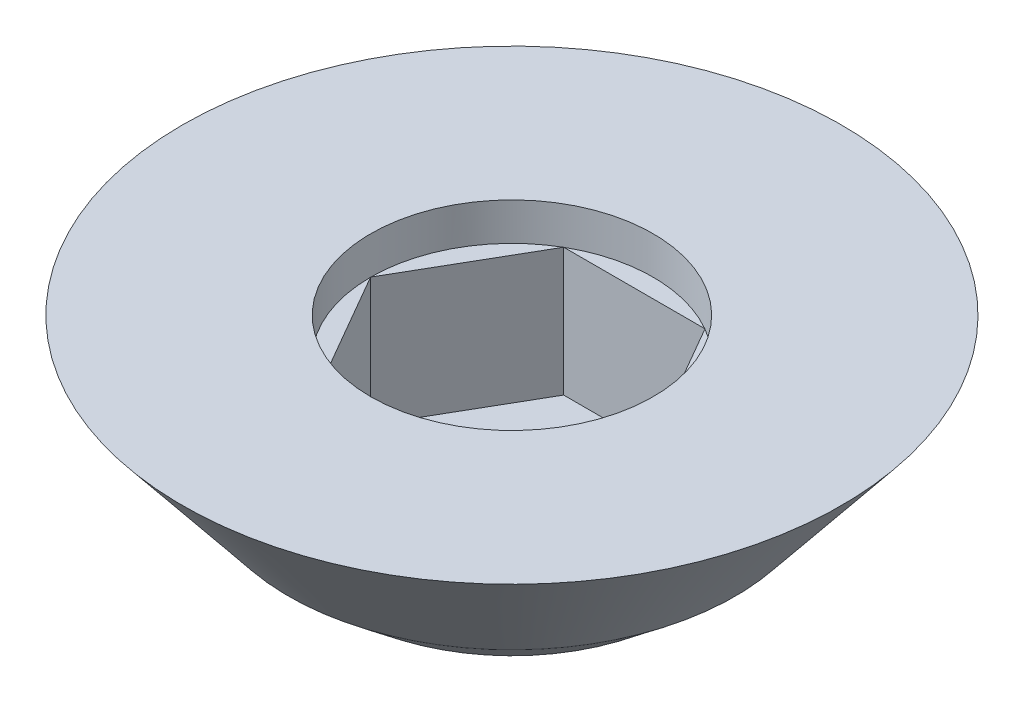
SolidWorks part; units mm, degrees
material "ABS"
ref_plane "Piano frontale" through (0, 0, 0) normal (0, 0, 1) x (1, 0, 0)
ref_plane "Piano superiore" through (0, 0, 0) normal (0, 1, 0) x (1, 0, 0)
ref_plane "Piano destro" through (0, 0, 0) normal (1, 0, 0) x (0, 0, -1)
sketch "Schizzo3" plane through (0, 0, 0) normal (0, 0, 1) x (1, 0, 0)
  line L0 (0, 0) -> (-10, 0) construction
  line L1 (-10, 0) -> (-17.5, 9.3) construction
  line L2 (-17.5, 9.3) -> (0, 9.3)
  line L3 (0, 9.3) -> (0, 0)
  line L4 (-11.8502, 2.2943) -> (-9, 0)
  line L5 (-11.8502, 2.2943) -> (-17.5, 9.3)
  line L6 (-9, 0) -> (0, 0)
  dimension "D1" = 9.3
  dimension "D2" = 10
  dimension "D3" = 17.5
  dimension "D4" = 9
  dimension "D5" = 9
revolve "Rivoluzione1" add sketch "Schizzo3" angle 360 about L3
sketch "Schizzo4" plane through (0, 9.3, 0) normal (0, 1, 0) x (1, 0, 0)
  circle A0 centre (0, 0) radius 7.5
  dimension "D1" = 15
extrude "Taglio-Estrusione1" cut sketch "Schizzo4" against normal blind 2
sketch "Schizzo5" plane through (0, 7.3, 0) normal (0, 1, 0) x (1, 0, 0)
  line L1 (3.7528, -6.5) -> (7.5056, 0)
  line L2 (7.5056, 0) -> (3.7528, 6.5)
  line L3 (3.7528, 6.5) -> (-3.7528, 6.5)
  line L4 (-3.7528, 6.5) -> (-7.5056, 0)
  line L5 (-7.5056, 0) -> (-3.7528, -6.5)
  line L6 (-3.7528, -6.5) -> (3.7528, -6.5)
  circle A0 centre (0, 0) radius 6.5 construction
  dimension "D1" = 13
extrude "Taglio-Estrusione2" cut sketch "Schizzo5" against normal blind 6.8
